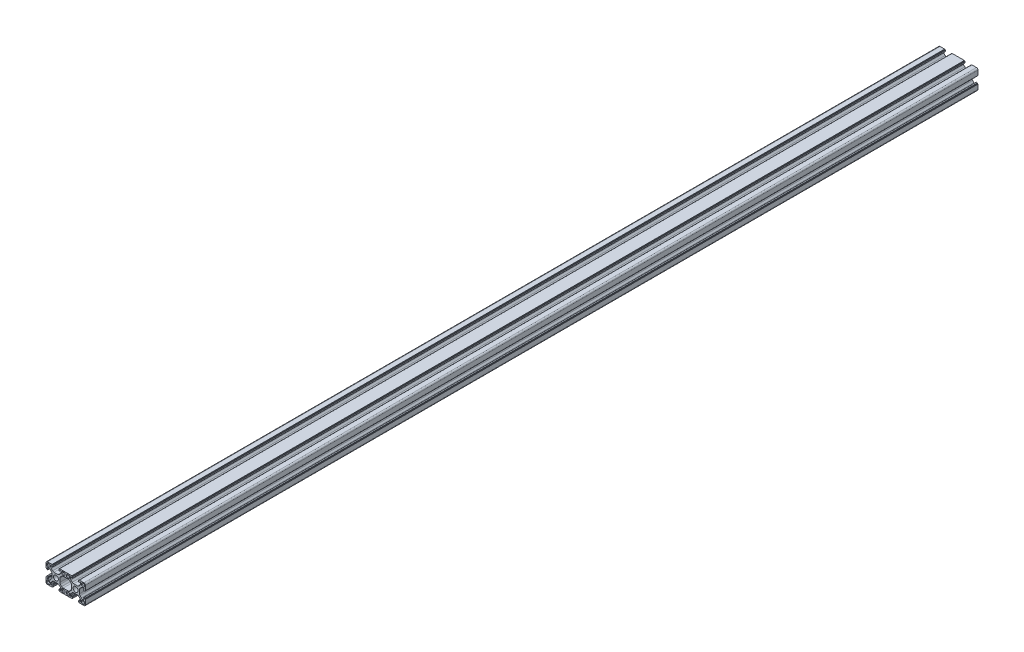
SolidWorks part; units mm, degrees
material "1060 Сплав"
ref_plane "Спереди" through (0, 0, 0) normal (0, 0, 1) x (1, 0, 0)
ref_plane "Сверху" through (0, 0, 0) normal (0, 1, 0) x (1, 0, 0)
ref_plane "Справа" through (0, 0, 0) normal (1, 0, 0) x (0, 0, -1)
sketch "Эскиз1" plane through (0, 0, 0) normal (0, 0, 1) x (1, 0, 0)
  line L0 (-13.2851, 26.791) -> (-11.7851, 25.291) construction
  line L1 (8.2149, 28.291) -> (5.2149, 25.291) construction
  line L2 (-20.8851, 19.191) -> (-10.8851, 29.191) construction
  line L3 (-0.8851, 23.191) -> (1.0137, 23.191)
  line L4 (-0.8851, 19.191) -> (9.1149, 29.191) construction
  line L5 (6.7149, 26.791) -> (5.2149, 28.291) construction
  line L6 (2.4279, 23.7768) -> (3.7291, 25.078)
  line L7 (6.0149, 25.291) -> (7.4149, 25.291)
  line L8 (5.2149, 26.091) -> (5.2149, 27.491)
  line L9 (7.4149, 28.291) -> (6.0149, 28.291)
  line L10 (4.3149, 27.391) -> (4.3149, 26.4922)
  line L11 (2.8781, 27.2642) -> (3.3584, 27.7445)
  line L12 (2.3149, 28.74) -> (2.8149, 28.74)
  line L13 (2.7013, 27.191) -> (2.4149, 27.191)
  line L14 (3.712, 27.891) -> (3.8149, 27.891)
  line L15 (2.8149, 29.041) -> (2.8149, 28.74)
  line L16 (2.1649, 28.59) -> (2.1649, 27.441)
  line L17 (7.6149, 29.191) -> (2.9649, 29.191)
  line L18 (8.2149, 27.491) -> (8.2149, 26.091)
  line L19 (9.1149, 27.691) -> (9.1149, 23.041)
  line L20 (8.514, 22.241) -> (7.3649, 22.241)
  line L21 (8.9649, 22.891) -> (8.664, 22.891)
  line L22 (7.8149, 23.7881) -> (7.8149, 23.891)
  line L23 (7.1149, 22.7774) -> (7.1149, 22.491)
  line L24 (8.664, 22.391) -> (8.664, 22.891)
  line L25 (7.1881, 22.9542) -> (7.6684, 23.4345)
  line L26 (7.3149, 24.391) -> (6.4161, 24.391)
  line L27 (3.7007, 22.504) -> (5.0019, 23.8052)
  line L28 (3.1149, 19.191) -> (3.1149, 21.0898)
  line L29 (3.1149, 19.191) -> (3.1149, 17.2922)
  line L30 (3.7007, 15.878) -> (5.0019, 14.5768)
  line L31 (5.2149, 12.291) -> (5.2149, 10.891)
  line L32 (6.0149, 13.091) -> (7.4149, 13.091)
  line L33 (8.2149, 10.891) -> (8.2149, 12.291)
  line L34 (7.3149, 13.991) -> (6.4161, 13.991)
  line L35 (7.1881, 15.4278) -> (7.6684, 14.9474)
  line L36 (8.664, 15.991) -> (8.664, 15.491)
  line L37 (7.1149, 15.6045) -> (7.1149, 15.891)
  line L38 (7.8149, 14.5939) -> (7.8149, 14.491)
  line L39 (8.9649, 15.491) -> (8.664, 15.491)
  line L40 (8.514, 16.141) -> (7.3649, 16.141)
  line L41 (9.1149, 10.691) -> (9.1149, 15.341)
  line L42 (7.4149, 10.091) -> (6.0149, 10.091)
  line L43 (7.6149, 9.191) -> (2.9649, 9.191)
  line L44 (2.1649, 9.7919) -> (2.1649, 10.941)
  line L45 (2.8149, 9.341) -> (2.8149, 9.6419)
  line L46 (3.712, 10.491) -> (3.8149, 10.491)
  line L47 (2.7013, 11.191) -> (2.4149, 11.191)
  line L48 (2.3149, 9.6419) -> (2.8149, 9.6419)
  line L49 (2.8781, 11.1178) -> (3.3584, 10.6374)
  line L50 (4.3149, 10.991) -> (4.3149, 11.8898)
  line L51 (2.4279, 14.6052) -> (3.7291, 13.304)
  line L52 (-0.8851, 15.191) -> (1.0137, 15.191)
  line L53 (8.2149, 10.091) -> (5.2149, 13.091) construction
  line L54 (-0.8851, 19.191) -> (9.1149, 9.191) construction
  line L55 (6.7149, 11.591) -> (8.2149, 13.091) construction
  line L56 (-0.8851, 15.191) -> (-2.7839, 15.191)
  line L57 (-4.1981, 14.6052) -> (-5.4993, 13.304)
  line L58 (-7.7851, 13.091) -> (-9.1851, 13.091)
  line L59 (-6.9851, 12.291) -> (-6.9851, 10.891)
  line L60 (-9.1851, 10.091) -> (-7.7851, 10.091)
  line L61 (-6.0851, 10.991) -> (-6.0851, 11.8898)
  line L62 (-4.6483, 11.1178) -> (-5.1287, 10.6374)
  line L63 (-4.0851, 9.6419) -> (-4.5851, 9.6419)
  line L64 (-4.4716, 11.191) -> (-4.1851, 11.191)
  line L65 (-5.4822, 10.491) -> (-5.5851, 10.491)
  line L66 (-4.5851, 9.341) -> (-4.5851, 9.6419)
  line L67 (-3.9351, 9.7919) -> (-3.9351, 10.941)
  line L68 (-9.3851, 9.191) -> (-4.7351, 9.191)
  line L69 (-9.9851, 10.891) -> (-9.9851, 12.291)
  line L70 (-9.0851, 13.991) -> (-8.1863, 13.991)
  line L71 (-5.4709, 15.878) -> (-6.7721, 14.5768)
  line L72 (-4.8851, 19.191) -> (-4.8851, 17.2922)
  line L73 (-11.7851, 28.291) -> (-14.7851, 25.291) construction
  line L74 (-9.9851, 10.091) -> (-6.9851, 13.091) construction
  line L75 (-13.2851, 11.591) -> (-14.7851, 10.091) construction
  line L76 (-0.8851, 19.191) -> (-10.8851, 9.191) construction
  line L77 (-8.4851, 11.591) -> (-6.9851, 10.091) construction
  line L78 (-4.8851, 19.191) -> (-4.8851, 21.0898)
  line L79 (-5.4709, 22.504) -> (-6.7721, 23.8052)
  line L80 (-6.9851, 26.091) -> (-6.9851, 27.491)
  line L81 (-7.7851, 25.291) -> (-9.1851, 25.291)
  line L82 (-9.9851, 27.491) -> (-9.9851, 26.091)
  line L83 (-9.0851, 24.391) -> (-8.1863, 24.391)
  line L84 (-9.1851, 28.291) -> (-7.7851, 28.291)
  line L85 (-9.3851, 29.191) -> (-4.7351, 29.191)
  line L86 (-3.9351, 28.59) -> (-3.9351, 27.441)
  line L87 (-4.5851, 29.041) -> (-4.5851, 28.74)
  line L88 (-5.4822, 27.891) -> (-5.5851, 27.891)
  line L89 (-4.4716, 27.191) -> (-4.1851, 27.191)
  line L90 (-4.0851, 28.74) -> (-4.5851, 28.74)
  line L91 (-4.6483, 27.2642) -> (-5.1287, 27.7445)
  line L92 (-6.0851, 27.391) -> (-6.0851, 26.4922)
  line L93 (-4.1981, 23.7768) -> (-5.4993, 25.078)
  line L94 (-0.8851, 23.191) -> (-2.7839, 23.191)
  line L95 (-12.6492, 19.191) -> (10.6192, 19.191) construction
  line L96 (-9.9851, 28.291) -> (-6.9851, 25.291) construction
  line L97 (-0.8851, 7.1046) -> (-0.8851, 29.9099) construction
  line L98 (-0.8851, 19.191) -> (-10.8851, 29.191) construction
  line L99 (-8.4851, 26.791) -> (-9.9851, 25.291) construction
  line L100 (-20.8851, 19.191) -> (-10.8851, 9.191) construction
  line L101 (-11.7851, 10.091) -> (-14.7851, 13.091) construction
  line L102 (-28.4851, 11.591) -> (-29.9851, 13.091) construction
  line L103 (-20.8851, 19.191) -> (-30.8851, 9.191) construction
  line L104 (-29.9851, 10.091) -> (-26.9851, 13.091) construction
  line L105 (-28.4851, 26.791) -> (-26.9851, 28.291) construction
  line L106 (-20.8851, 19.191) -> (-30.8851, 29.191) construction
  line L107 (-29.9851, 28.291) -> (-26.9851, 25.291) construction
  line L108 (-20.8851, 23.191) -> (-18.9863, 23.191)
  line L109 (-17.5721, 23.7768) -> (-16.2709, 25.078)
  line L110 (-15.6851, 27.391) -> (-15.6851, 26.4922)
  line L111 (-17.1219, 27.2642) -> (-16.6416, 27.7445)
  line L112 (-17.6851, 28.74) -> (-17.1851, 28.74)
  line L113 (-17.2987, 27.191) -> (-17.5851, 27.191)
  line L114 (-16.288, 27.891) -> (-16.1851, 27.891)
  line L115 (-17.1851, 29.041) -> (-17.1851, 28.74)
  line L116 (-17.8351, 28.59) -> (-17.8351, 27.441)
  line L117 (-12.3851, 29.191) -> (-17.0351, 29.191)
  line L118 (-12.5851, 28.291) -> (-13.9851, 28.291)
  line L119 (-12.6851, 24.391) -> (-13.5839, 24.391)
  line L120 (-11.7851, 27.491) -> (-11.7851, 26.091)
  line L121 (-13.9851, 25.291) -> (-12.5851, 25.291)
  line L122 (-14.7851, 26.091) -> (-14.7851, 27.491)
  line L123 (-16.2993, 22.504) -> (-14.9981, 23.8052)
  line L124 (-16.8851, 19.191) -> (-16.8851, 21.0898)
  line L125 (-16.8851, 19.191) -> (-16.8851, 17.2922)
  line L126 (-16.2993, 15.878) -> (-14.9981, 14.5768)
  line L127 (-12.6851, 13.991) -> (-13.5839, 13.991)
  line L128 (-11.7851, 10.891) -> (-11.7851, 12.291)
  line L129 (-12.3851, 9.191) -> (-17.0351, 9.191)
  line L130 (-17.8351, 9.7919) -> (-17.8351, 10.941)
  line L131 (-17.1851, 9.341) -> (-17.1851, 9.6419)
  line L132 (-16.288, 10.491) -> (-16.1851, 10.491)
  line L133 (-17.2987, 11.191) -> (-17.5851, 11.191)
  line L134 (-17.6851, 9.6419) -> (-17.1851, 9.6419)
  line L135 (-17.1219, 11.1178) -> (-16.6416, 10.6374)
  line L136 (-15.6851, 10.991) -> (-15.6851, 11.8898)
  line L137 (-12.5851, 10.091) -> (-13.9851, 10.091)
  line L138 (-14.7851, 12.291) -> (-14.7851, 10.891)
  line L139 (-13.9851, 13.091) -> (-12.5851, 13.091)
  line L140 (-17.5721, 14.6052) -> (-16.2709, 13.304)
  line L141 (-20.8851, 15.191) -> (-18.9863, 15.191)
  line L142 (-20.8851, 15.191) -> (-22.7839, 15.191)
  line L143 (-24.1981, 14.6052) -> (-25.4993, 13.304)
  line L144 (-26.0851, 10.991) -> (-26.0851, 11.8898)
  line L145 (-24.6483, 11.1178) -> (-25.1287, 10.6374)
  line L146 (-24.0851, 9.6419) -> (-24.5851, 9.6419)
  line L147 (-24.4716, 11.191) -> (-24.1851, 11.191)
  line L148 (-25.4822, 10.491) -> (-25.5851, 10.491)
  line L149 (-24.5851, 9.341) -> (-24.5851, 9.6419)
  line L150 (-23.9351, 9.7919) -> (-23.9351, 10.941)
  line L151 (-29.3851, 9.191) -> (-24.7351, 9.191)
  line L152 (-29.1851, 10.091) -> (-27.7851, 10.091)
  line L153 (-30.8851, 10.691) -> (-30.8851, 15.341)
  line L154 (-30.2842, 16.141) -> (-29.1351, 16.141)
  line L155 (-30.7351, 15.491) -> (-30.4342, 15.491)
  line L156 (-29.5851, 14.5939) -> (-29.5851, 14.491)
  line L157 (-28.8851, 15.6045) -> (-28.8851, 15.891)
  line L158 (-30.4342, 15.991) -> (-30.4342, 15.491)
  line L159 (-28.9583, 15.4278) -> (-29.4387, 14.9474)
  line L160 (-29.0851, 13.991) -> (-28.1863, 13.991)
  line L161 (-29.9851, 10.891) -> (-29.9851, 12.291)
  line L162 (-27.7851, 13.091) -> (-29.1851, 13.091)
  line L163 (-26.9851, 12.291) -> (-26.9851, 10.891)
  line L164 (-25.4709, 15.878) -> (-26.7721, 14.5768)
  line L165 (-24.8851, 19.191) -> (-24.8851, 17.2922)
  line L166 (-24.8851, 19.191) -> (-24.8851, 21.0898)
  line L167 (-25.4709, 22.504) -> (-26.7721, 23.8052)
  line L168 (-29.0851, 24.391) -> (-28.1863, 24.391)
  line L169 (-28.9583, 22.9542) -> (-29.4387, 23.4345)
  line L170 (-30.4342, 22.391) -> (-30.4342, 22.891)
  line L171 (-28.8851, 22.7774) -> (-28.8851, 22.491)
  line L172 (-29.5851, 23.7881) -> (-29.5851, 23.891)
  line L173 (-30.7351, 22.891) -> (-30.4342, 22.891)
  line L174 (-30.2842, 22.241) -> (-29.1351, 22.241)
  line L175 (-30.8851, 27.691) -> (-30.8851, 23.041)
  line L176 (-29.9851, 27.491) -> (-29.9851, 26.091)
  line L177 (-29.3851, 29.191) -> (-24.7351, 29.191)
  line L178 (-23.9351, 28.59) -> (-23.9351, 27.441)
  line L179 (-24.5851, 29.041) -> (-24.5851, 28.74)
  line L180 (-25.4822, 27.891) -> (-25.5851, 27.891)
  line L181 (-24.4716, 27.191) -> (-24.1851, 27.191)
  line L182 (-24.0851, 28.74) -> (-24.5851, 28.74)
  line L183 (-24.6483, 27.2642) -> (-25.1287, 27.7445)
  line L184 (-26.0851, 27.391) -> (-26.0851, 26.4922)
  line L185 (-29.1851, 28.291) -> (-27.7851, 28.291)
  line L186 (-26.9851, 26.091) -> (-26.9851, 27.491)
  line L187 (-27.7851, 25.291) -> (-29.1851, 25.291)
  line L188 (-24.1981, 23.7768) -> (-25.4993, 25.078)
  line L189 (-20.8851, 23.191) -> (-22.7839, 23.191)
  line L190 (-12.3851, 9.191) -> (-9.3851, 9.191)
  line L191 (-12.6851, 13.991) -> (-9.0851, 13.991)
  line L192 (-12.6851, 24.391) -> (-9.0851, 24.391)
  line L193 (-12.3851, 29.191) -> (-9.3851, 29.191)
  arc A0 (8.2149, 27.491) -> (7.4149, 28.291) centre (7.4149, 27.491) ccw
  arc A1 (6.0149, 28.291) -> (5.2149, 27.491) centre (6.0149, 27.491) ccw
  arc A2 (6.0149, 25.291) -> (5.2149, 26.091) centre (6.0149, 26.091) cw
  arc A3 (7.6149, 29.191) -> (9.1149, 27.691) centre (7.6149, 27.691) cw
  arc A4 (2.3149, 28.74) -> (2.1649, 28.59) centre (2.3149, 28.59) ccw
  arc A5 (2.9649, 29.191) -> (2.8149, 29.041) centre (2.9649, 29.041) ccw
  arc A6 (2.7013, 27.191) -> (2.8781, 27.2642) centre (2.7013, 27.441) ccw
  arc A7 (2.4149, 27.191) -> (2.1649, 27.441) centre (2.4149, 27.441) cw
  arc A8 (3.3584, 27.7445) -> (3.712, 27.891) centre (3.712, 27.391) cw
  arc A9 (3.8149, 27.891) -> (4.3149, 27.391) centre (3.8149, 27.391) cw
  arc A10 (1.6149, 19.191) -> (-0.8851, 21.691) centre (-0.8851, 19.191) ccw
  arc A11 (1.0137, 23.191) -> (2.4279, 23.7768) centre (1.0137, 25.191) ccw
  arc A12 (4.3149, 26.4922) -> (3.7291, 25.078) centre (2.3149, 26.4922) cw
  arc A13 (8.2149, 26.091) -> (7.4149, 25.291) centre (7.4149, 26.091) cw
  arc A14 (7.8149, 23.891) -> (7.3149, 24.391) centre (7.3149, 23.891) ccw
  arc A15 (7.6684, 23.4345) -> (7.8149, 23.7881) centre (7.3149, 23.7881) ccw
  arc A16 (7.1149, 22.491) -> (7.3649, 22.241) centre (7.3649, 22.491) ccw
  arc A17 (7.1149, 22.7774) -> (7.1881, 22.9542) centre (7.3649, 22.7774) cw
  arc A18 (9.1149, 23.041) -> (8.9649, 22.891) centre (8.9649, 23.041) cw
  arc A19 (8.664, 22.391) -> (8.514, 22.241) centre (8.514, 22.391) cw
  arc A20 (6.4161, 24.391) -> (5.0019, 23.8052) centre (6.4161, 22.391) ccw
  arc A21 (3.1149, 21.0898) -> (3.7007, 22.504) centre (5.1149, 21.0898) cw
  arc A22 (7.4149, 10.091) -> (8.2149, 10.891) centre (7.4149, 10.891) ccw
  arc A23 (8.2149, 12.291) -> (7.4149, 13.091) centre (7.4149, 12.291) ccw
  arc A24 (5.2149, 12.291) -> (6.0149, 13.091) centre (6.0149, 12.291) cw
  arc A25 (9.1149, 10.691) -> (7.6149, 9.191) centre (7.6149, 10.691) cw
  arc A26 (8.664, 15.991) -> (8.514, 16.141) centre (8.514, 15.991) ccw
  arc A27 (9.1149, 15.341) -> (8.9649, 15.491) centre (8.9649, 15.341) ccw
  arc A28 (7.1149, 15.6045) -> (7.1881, 15.4278) centre (7.3649, 15.6045) ccw
  arc A29 (7.1149, 15.891) -> (7.3649, 16.141) centre (7.3649, 15.891) cw
  arc A30 (7.6684, 14.9474) -> (7.8149, 14.5939) centre (7.3149, 14.5939) cw
  arc A31 (7.8149, 14.491) -> (7.3149, 13.991) centre (7.3149, 14.491) cw
  arc A32 (-0.8851, 16.691) -> (1.6149, 19.191) centre (-0.8851, 19.191) ccw
  arc A33 (3.1149, 17.2922) -> (3.7007, 15.878) centre (5.1149, 17.2922) ccw
  arc A34 (6.4161, 13.991) -> (5.0019, 14.5768) centre (6.4161, 15.991) cw
  arc A35 (6.0149, 10.091) -> (5.2149, 10.891) centre (6.0149, 10.891) cw
  arc A36 (3.8149, 10.491) -> (4.3149, 10.991) centre (3.8149, 10.991) ccw
  arc A37 (3.3584, 10.6374) -> (3.712, 10.491) centre (3.712, 10.991) ccw
  arc A38 (2.4149, 11.191) -> (2.1649, 10.941) centre (2.4149, 10.941) ccw
  arc A39 (2.7013, 11.191) -> (2.8781, 11.1178) centre (2.7013, 10.941) cw
  arc A40 (2.9649, 9.191) -> (2.8149, 9.341) centre (2.9649, 9.341) cw
  arc A41 (2.3149, 9.6419) -> (2.1649, 9.7919) centre (2.3149, 9.7919) cw
  arc A42 (4.3149, 11.8898) -> (3.7291, 13.304) centre (2.3149, 11.8898) ccw
  arc A43 (1.0137, 15.191) -> (2.4279, 14.6052) centre (1.0137, 13.191) cw
  arc A44 (-9.9851, 10.891) -> (-9.1851, 10.091) centre (-9.1851, 10.891) ccw
  arc A45 (-7.7851, 10.091) -> (-6.9851, 10.891) centre (-7.7851, 10.891) ccw
  arc A46 (-7.7851, 13.091) -> (-6.9851, 12.291) centre (-7.7851, 12.291) cw
  arc A47 (-4.0851, 9.6419) -> (-3.9351, 9.7919) centre (-4.0851, 9.7919) ccw
  arc A48 (-4.7351, 9.191) -> (-4.5851, 9.341) centre (-4.7351, 9.341) ccw
  arc A49 (-4.4716, 11.191) -> (-4.6483, 11.1178) centre (-4.4716, 10.941) ccw
  arc A50 (-4.1851, 11.191) -> (-3.9351, 10.941) centre (-4.1851, 10.941) cw
  arc A51 (-5.1287, 10.6374) -> (-5.4822, 10.491) centre (-5.4822, 10.991) cw
  arc A52 (-5.5851, 10.491) -> (-6.0851, 10.991) centre (-5.5851, 10.991) cw
  arc A53 (-3.3851, 19.191) -> (-0.8851, 16.691) centre (-0.8851, 19.191) ccw
  arc A54 (-2.7839, 15.191) -> (-4.1981, 14.6052) centre (-2.7839, 13.191) ccw
  arc A55 (-6.0851, 11.8898) -> (-5.4993, 13.304) centre (-4.0851, 11.8898) cw
  arc A56 (-9.9851, 12.291) -> (-9.1851, 13.091) centre (-9.1851, 12.291) cw
  arc A57 (-8.1863, 13.991) -> (-6.7721, 14.5768) centre (-8.1863, 15.991) ccw
  arc A58 (-4.8851, 17.2922) -> (-5.4709, 15.878) centre (-6.8851, 17.2922) cw
  arc A59 (-9.1851, 28.291) -> (-9.9851, 27.491) centre (-9.1851, 27.491) ccw
  arc A60 (-9.9851, 26.091) -> (-9.1851, 25.291) centre (-9.1851, 26.091) ccw
  arc A61 (-6.9851, 26.091) -> (-7.7851, 25.291) centre (-7.7851, 26.091) cw
  arc A62 (-0.8851, 21.691) -> (-3.3851, 19.191) centre (-0.8851, 19.191) ccw
  arc A63 (-4.8851, 21.0898) -> (-5.4709, 22.504) centre (-6.8851, 21.0898) ccw
  arc A64 (-8.1863, 24.391) -> (-6.7721, 23.8052) centre (-8.1863, 22.391) cw
  arc A65 (-7.7851, 28.291) -> (-6.9851, 27.491) centre (-7.7851, 27.491) cw
  arc A66 (-5.5851, 27.891) -> (-6.0851, 27.391) centre (-5.5851, 27.391) ccw
  arc A67 (-5.1287, 27.7445) -> (-5.4822, 27.891) centre (-5.4822, 27.391) ccw
  arc A68 (-4.1851, 27.191) -> (-3.9351, 27.441) centre (-4.1851, 27.441) ccw
  arc A69 (-4.4716, 27.191) -> (-4.6483, 27.2642) centre (-4.4716, 27.441) cw
  arc A70 (-4.7351, 29.191) -> (-4.5851, 29.041) centre (-4.7351, 29.041) cw
  arc A71 (-4.0851, 28.74) -> (-3.9351, 28.59) centre (-4.0851, 28.59) cw
  arc A72 (-6.0851, 26.4922) -> (-5.4993, 25.078) centre (-4.0851, 26.4922) ccw
  arc A73 (-2.7839, 23.191) -> (-4.1981, 23.7768) centre (-2.7839, 25.191) cw
  arc A74 (-18.9863, 23.191) -> (-17.5721, 23.7768) centre (-18.9863, 25.191) ccw
  arc A75 (-15.6851, 26.4922) -> (-16.2709, 25.078) centre (-17.6851, 26.4922) cw
  arc A76 (-17.6851, 28.74) -> (-17.8351, 28.59) centre (-17.6851, 28.59) ccw
  arc A77 (-17.0351, 29.191) -> (-17.1851, 29.041) centre (-17.0351, 29.041) ccw
  arc A78 (-17.2987, 27.191) -> (-17.1219, 27.2642) centre (-17.2987, 27.441) ccw
  arc A79 (-17.5851, 27.191) -> (-17.8351, 27.441) centre (-17.5851, 27.441) cw
  arc A80 (-16.6416, 27.7445) -> (-16.288, 27.891) centre (-16.288, 27.391) cw
  arc A81 (-16.1851, 27.891) -> (-15.6851, 27.391) centre (-16.1851, 27.391) cw
  arc A82 (-13.9851, 28.291) -> (-14.7851, 27.491) centre (-13.9851, 27.491) ccw
  arc A83 (-13.5839, 24.391) -> (-14.9981, 23.8052) centre (-13.5839, 22.391) ccw
  arc A84 (-16.8851, 21.0898) -> (-16.2993, 22.504) centre (-14.8851, 21.0898) cw
  arc A85 (-20.8851, 21.691) -> (-18.3851, 19.191) centre (-20.8851, 19.191) cw
  arc A86 (-14.7851, 26.091) -> (-13.9851, 25.291) centre (-13.9851, 26.091) ccw
  arc A87 (-11.7851, 26.091) -> (-12.5851, 25.291) centre (-12.5851, 26.091) cw
  arc A88 (-12.5851, 28.291) -> (-11.7851, 27.491) centre (-12.5851, 27.491) cw
  arc A89 (-16.8851, 17.2922) -> (-16.2993, 15.878) centre (-14.8851, 17.2922) ccw
  arc A90 (-13.5839, 13.991) -> (-14.9981, 14.5768) centre (-13.5839, 15.991) cw
  arc A91 (-11.7851, 12.291) -> (-12.5851, 13.091) centre (-12.5851, 12.291) ccw
  arc A92 (-15.6851, 11.8898) -> (-16.2709, 13.304) centre (-17.6851, 11.8898) ccw
  arc A93 (-18.9863, 15.191) -> (-17.5721, 14.6052) centre (-18.9863, 13.191) cw
  arc A94 (-18.3851, 19.191) -> (-20.8851, 16.691) centre (-20.8851, 19.191) cw
  arc A95 (-16.1851, 10.491) -> (-15.6851, 10.991) centre (-16.1851, 10.991) ccw
  arc A96 (-16.6416, 10.6374) -> (-16.288, 10.491) centre (-16.288, 10.991) ccw
  arc A97 (-17.5851, 11.191) -> (-17.8351, 10.941) centre (-17.5851, 10.941) ccw
  arc A98 (-17.2987, 11.191) -> (-17.1219, 11.1178) centre (-17.2987, 10.941) cw
  arc A99 (-17.0351, 9.191) -> (-17.1851, 9.341) centre (-17.0351, 9.341) cw
  arc A100 (-17.6851, 9.6419) -> (-17.8351, 9.7919) centre (-17.6851, 9.7919) cw
  arc A101 (-13.9851, 13.091) -> (-14.7851, 12.291) centre (-13.9851, 12.291) ccw
  arc A102 (-13.9851, 10.091) -> (-14.7851, 10.891) centre (-13.9851, 10.891) cw
  arc A103 (-11.7851, 10.891) -> (-12.5851, 10.091) centre (-12.5851, 10.891) cw
  arc A104 (-22.7839, 15.191) -> (-24.1981, 14.6052) centre (-22.7839, 13.191) ccw
  arc A105 (-26.0851, 11.8898) -> (-25.4993, 13.304) centre (-24.0851, 11.8898) cw
  arc A106 (-24.0851, 9.6419) -> (-23.9351, 9.7919) centre (-24.0851, 9.7919) ccw
  arc A107 (-24.7351, 9.191) -> (-24.5851, 9.341) centre (-24.7351, 9.341) ccw
  arc A108 (-24.4716, 11.191) -> (-24.6483, 11.1178) centre (-24.4716, 10.941) ccw
  arc A109 (-24.1851, 11.191) -> (-23.9351, 10.941) centre (-24.1851, 10.941) cw
  arc A110 (-25.1287, 10.6374) -> (-25.4822, 10.491) centre (-25.4822, 10.991) cw
  arc A111 (-25.5851, 10.491) -> (-26.0851, 10.991) centre (-25.5851, 10.991) cw
  arc A112 (-27.7851, 10.091) -> (-26.9851, 10.891) centre (-27.7851, 10.891) ccw
  arc A113 (-28.1863, 13.991) -> (-26.7721, 14.5768) centre (-28.1863, 15.991) ccw
  arc A114 (-24.8851, 17.2922) -> (-25.4709, 15.878) centre (-26.8851, 17.2922) cw
  arc A115 (-20.8851, 16.691) -> (-23.3851, 19.191) centre (-20.8851, 19.191) cw
  arc A116 (-29.5851, 14.491) -> (-29.0851, 13.991) centre (-29.0851, 14.491) ccw
  arc A117 (-29.4387, 14.9474) -> (-29.5851, 14.5939) centre (-29.0851, 14.5939) ccw
  arc A118 (-28.8851, 15.891) -> (-29.1351, 16.141) centre (-29.1351, 15.891) ccw
  arc A119 (-28.8851, 15.6045) -> (-28.9583, 15.4278) centre (-29.1351, 15.6045) cw
  arc A120 (-30.8851, 15.341) -> (-30.7351, 15.491) centre (-30.7351, 15.341) cw
  arc A121 (-30.4342, 15.991) -> (-30.2842, 16.141) centre (-30.2842, 15.991) cw
  arc A122 (-30.8851, 10.691) -> (-29.3851, 9.191) centre (-29.3851, 10.691) ccw
  arc A123 (-26.9851, 12.291) -> (-27.7851, 13.091) centre (-27.7851, 12.291) ccw
  arc A124 (-29.9851, 12.291) -> (-29.1851, 13.091) centre (-29.1851, 12.291) cw
  arc A125 (-29.1851, 10.091) -> (-29.9851, 10.891) centre (-29.1851, 10.891) cw
  arc A126 (-24.8851, 21.0898) -> (-25.4709, 22.504) centre (-26.8851, 21.0898) ccw
  arc A127 (-28.1863, 24.391) -> (-26.7721, 23.8052) centre (-28.1863, 22.391) cw
  arc A128 (-30.4342, 22.391) -> (-30.2842, 22.241) centre (-30.2842, 22.391) ccw
  arc A129 (-30.8851, 23.041) -> (-30.7351, 22.891) centre (-30.7351, 23.041) ccw
  arc A130 (-28.8851, 22.7774) -> (-28.9583, 22.9542) centre (-29.1351, 22.7774) ccw
  arc A131 (-28.8851, 22.491) -> (-29.1351, 22.241) centre (-29.1351, 22.491) cw
  arc A132 (-29.4387, 23.4345) -> (-29.5851, 23.7881) centre (-29.0851, 23.7881) cw
  arc A133 (-29.5851, 23.891) -> (-29.0851, 24.391) centre (-29.0851, 23.891) cw
  arc A134 (-29.9851, 26.091) -> (-29.1851, 25.291) centre (-29.1851, 26.091) ccw
  arc A135 (-26.0851, 26.4922) -> (-25.4993, 25.078) centre (-24.0851, 26.4922) ccw
  arc A136 (-22.7839, 23.191) -> (-24.1981, 23.7768) centre (-22.7839, 25.191) cw
  arc A137 (-23.3851, 19.191) -> (-20.8851, 21.691) centre (-20.8851, 19.191) cw
  arc A138 (-25.5851, 27.891) -> (-26.0851, 27.391) centre (-25.5851, 27.391) ccw
  arc A139 (-25.1287, 27.7445) -> (-25.4822, 27.891) centre (-25.4822, 27.391) ccw
  arc A140 (-24.1851, 27.191) -> (-23.9351, 27.441) centre (-24.1851, 27.441) ccw
  arc A141 (-24.4716, 27.191) -> (-24.6483, 27.2642) centre (-24.4716, 27.441) cw
  arc A142 (-24.7351, 29.191) -> (-24.5851, 29.041) centre (-24.7351, 29.041) cw
  arc A143 (-24.0851, 28.74) -> (-23.9351, 28.59) centre (-24.0851, 28.59) cw
  arc A144 (-29.3851, 29.191) -> (-30.8851, 27.691) centre (-29.3851, 27.691) ccw
  arc A145 (-27.7851, 25.291) -> (-26.9851, 26.091) centre (-27.7851, 26.091) ccw
  arc A146 (-27.7851, 28.291) -> (-26.9851, 27.491) centre (-27.7851, 27.491) cw
  arc A147 (-29.9851, 27.491) -> (-29.1851, 28.291) centre (-29.1851, 27.491) cw
  point P0 (-0.8851, 19.191)
  point P12 (-0.8851, 19.191)
  point P45 (7.8149, 22.891)
  point P104 (2.8149, 10.491)
  point P155 (2.8149, 27.891)
  point P163 (7.8149, 15.491)
  point P164 (-0.8851, 15.2667)
  point P166 (-0.8851, 19.191)
  point P224 (-4.5851, 10.491)
  point P225 (-4.8094, 19.191)
  point P227 (-0.8851, 19.191)
  point P267 (-4.5851, 27.891)
  point P272 (3.0392, 19.191)
  point P288 (-0.8851, 23.1152)
  point P290 (-0.8851, 19.191)
  point P515 (-20.8851, 23.1152)
  point P516 (-24.8094, 19.191)
  point P517 (-17.1851, 27.891)
  point P518 (-16.9608, 19.191)
  point P519 (-17.1851, 10.491)
  point P520 (-20.8851, 15.2667)
  point P521 (-29.5851, 15.491)
  point P522 (-24.5851, 27.891)
  point P523 (-24.5851, 10.491)
  point P524 (-29.5851, 22.891)
  dimension "D3" = 5
  dimension "D6" = 2
  dimension "D1" = 2
  dimension "D2" = 6
  dimension "D4" = 4
  dimension "D5" = 0.9
extrude "Бобышка-Вытянуть1" add sketch "Эскиз1" along normal blind 905
